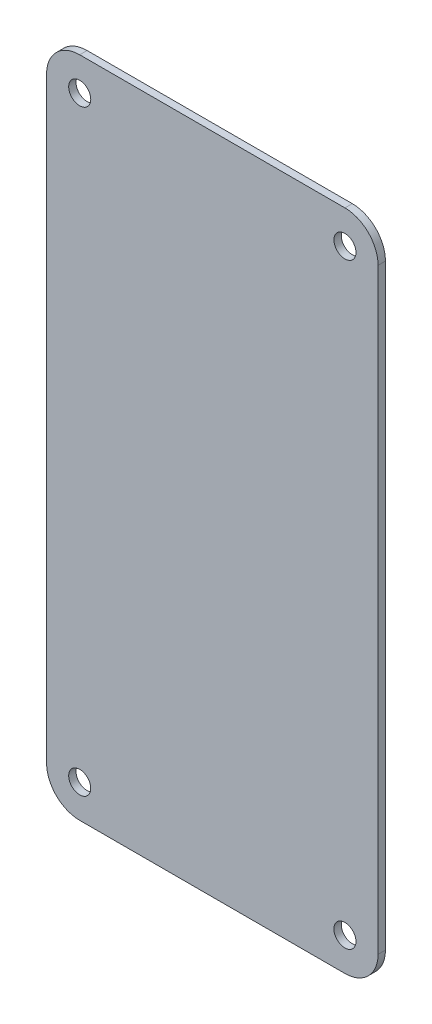
SolidWorks part; units mm, degrees
ref_plane "Alzado" through (0, 0, 0) normal (0, 0, 1) x (1, 0, 0)
ref_plane "Planta" through (0, 0, 0) normal (0, 1, 0) x (1, 0, 0)
ref_plane "Vista lateral" through (0, 0, 0) normal (1, 0, 0) x (0, 0, -1)
sketch "Model" plane through (0, 0, 0) normal (0, 0, 1) x (1, 0, 0)
  line L0 (-105.9434, 137.0565) -> (-105.9434, 56.0565)
  line L1 (-101.4434, 51.5565) -> (-65.4434, 51.5565)
  line L2 (-60.9434, 56.0565) -> (-60.9434, 137.0565)
  line L3 (-65.4434, 141.5565) -> (-101.4434, 141.5565)
  circle A0 centre (-101.4434, 137.0565) radius 1.5
  circle A1 centre (-65.4434, 137.0565) radius 1.5
  arc A2 (-101.4434, 141.5565) -> (-105.9434, 137.0565) centre (-101.4434, 137.0565) ccw
  arc A3 (-60.9434, 137.0565) -> (-65.4434, 141.5565) centre (-65.4434, 137.0565) ccw
  arc A4 (-105.9434, 56.0565) -> (-101.4434, 51.5565) centre (-101.4434, 56.0565) ccw
  arc A5 (-65.4434, 51.5565) -> (-60.9434, 56.0565) centre (-65.4434, 56.0565) ccw
  circle A6 centre (-101.4434, 56.0565) radius 1.5
  circle A7 centre (-65.4434, 56.0565) radius 1.5
extrude "Saliente-Extruir1" add sketch "Model" along normal blind 1
